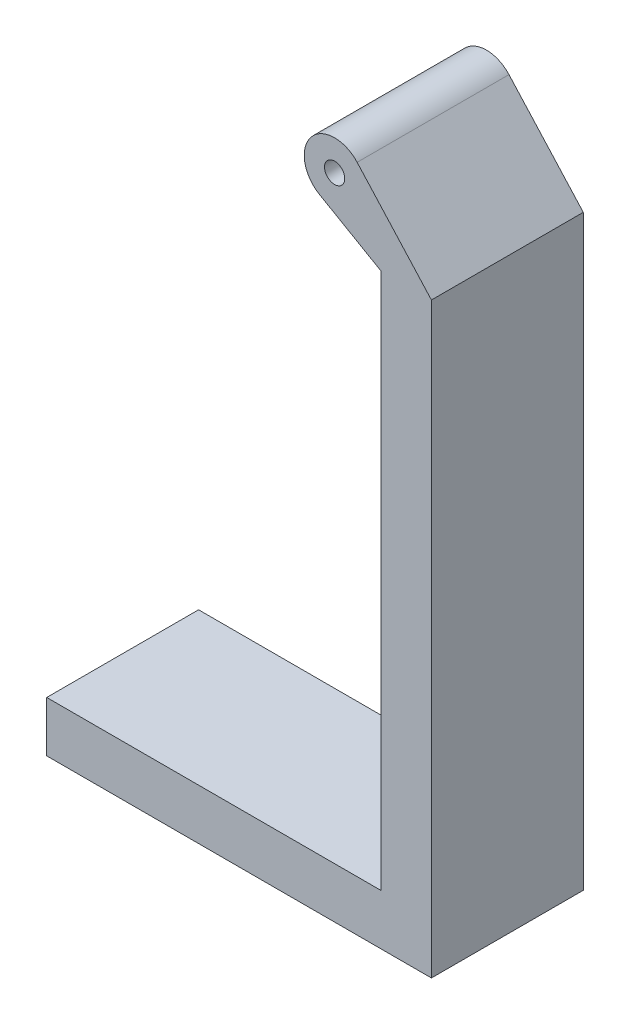
SolidWorks part; units mm, degrees
ref_plane "Front Plane" through (0, 0, 0) normal (0, 0, 1) x (1, 0, 0)
ref_plane "Top Plane" through (0, 0, 0) normal (0, 1, 0) x (1, 0, 0)
ref_plane "Right Plane" through (0, 0, 0) normal (1, 0, 0) x (0, 0, -1)
sketch "Sketch1" plane through (0, 0, 0) normal (0, 0, 1) x (1, 0, 0)
  line L0 (0, 0) -> (38, 0)
  line L1 (38, 0) -> (38, 58)
  line L2 (38, 58) -> (33, 58)
  line L3 (33, 58) -> (33, 5)
  line L4 (33, 5) -> (0, 5)
  line L5 (0, 5) -> (0, 0)
  dimension "D1" = 33
  dimension "D2" = 53
  dimension "D3" = 5
  dimension "D4" = 5
extrude "Boss-Extrude1" add sketch "Sketch1" along normal blind 15
sketch "Sketch2" plane through (0, 0, 15) normal (0, 0, 1) x (1, 0, 0)
  line L0 (33, 58) -> (26.9378, 61.5)
  line L1 (33, 58) -> (33, 5) construction
  line L2 (30.6625, 66.1107) -> (38, 58)
  line L3 (38, 58) -> (33, 58)
  arc A0 (26.9378, 61.5) -> (30.6625, 66.1107) centre (28.4378, 64.0981) cw
  dimension "D1" = 3
  dimension "D2" = 120
  dimension "D3" = 7
extrude "Boss-Extrude4" add sketch "Sketch2" against normal up to vertex (15 mm away) up to point (38, 58, 0)
sketch "Sketch3" plane through (0, 0, 15) normal (0, 0, 1) x (1, 0, 0)
  circle A0 centre (28.4378, 64.0981) radius 1
  arc A1 (30.6625, 66.1107) -> (26.9378, 61.5) centre (28.4378, 64.0981) ccw construction
  dimension "D1" = 2
extrude "Cut-Extrude1" cut sketch "Sketch3" against normal blind 25
